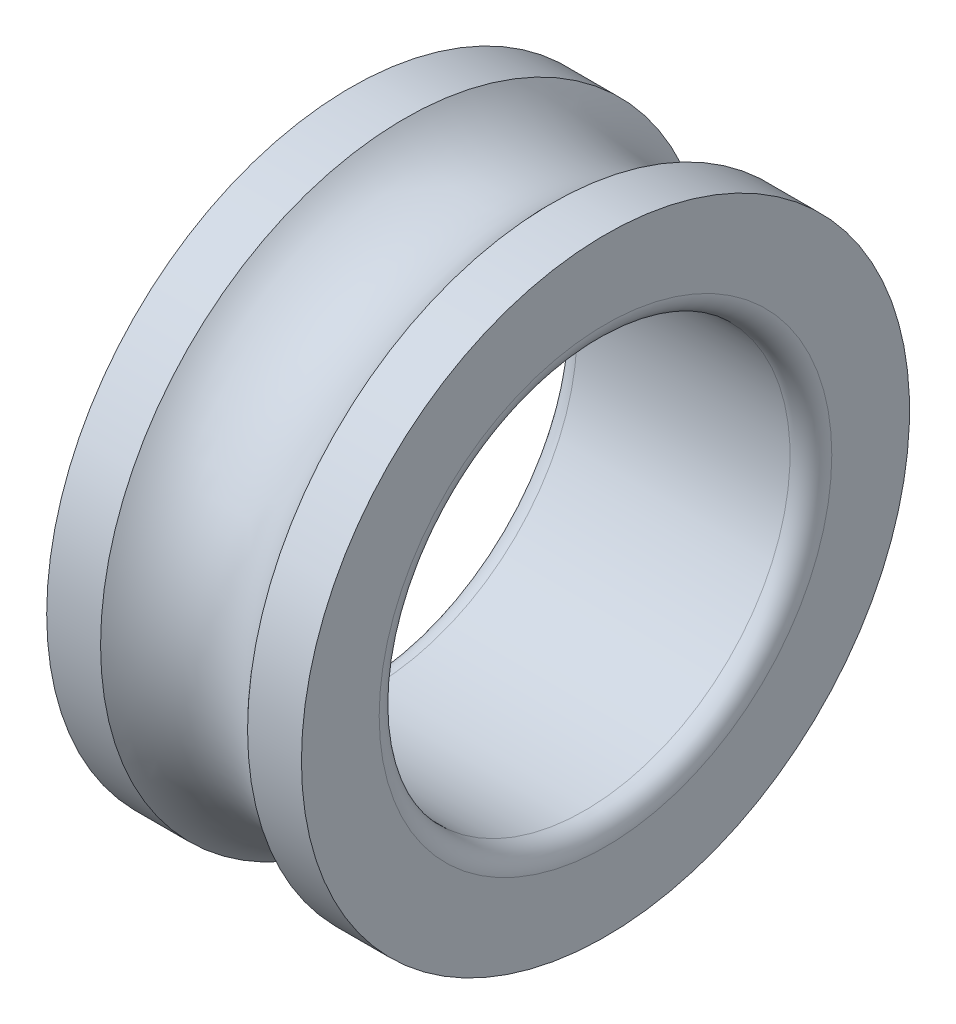
SolidWorks part; units mm, degrees
ref_plane "Front Plane" through (0, 0, 0) normal (0, 0, 1) x (1, 0, 0)
ref_plane "Top Plane" through (0, 0, 0) normal (0, 1, 0) x (1, 0, 0)
ref_plane "Right Plane" through (0, 0, 0) normal (1, 0, 0) x (0, 0, -1)
sketch "Sketch1" plane through (0, 0, 0) normal (0, 0, 1) x (1, 0, 0)
  line L0 (-21.6667, 0) -> (44, 0) construction
  line L1 (0, 25) -> (0, 0) construction
  line L2 (-15.5, 37) -> (-8.9443, 37)
  line L3 (-15.5, 37) -> (-15.5, 27.54)
  line L4 (-12.96, 25) -> (12.96, 25)
  line L5 (15.5, 37) -> (15.5, 27.54)
  line L6 (-15.5, 37) -> (15.5, 25) construction
  line L7 (-15.5, 25) -> (15.5, 37) construction
  line L8 (8.9443, 37) -> (15.5, 37)
  arc A0 (8.9443, 37) -> (-8.9443, 37) centre (0, 45) cw
  arc A1 (-15.5, 27.54) -> (-12.96, 25) centre (-12.96, 27.54) ccw
  arc A2 (12.96, 25) -> (15.5, 27.54) centre (12.96, 27.54) ccw
  point P3 (0, 31)
  dimension "D5" = 12
  dimension "D6" = 2.54
  dimension "D1" = 31
  dimension "D2" = 25
  dimension "D3" = 37
  dimension "D4" = 8
revolve "Revolve1" add sketch "Sketch1" angle 360 about L0
scale "Scale1" scale about centroid uniform scaling yes scale factor 0.07
